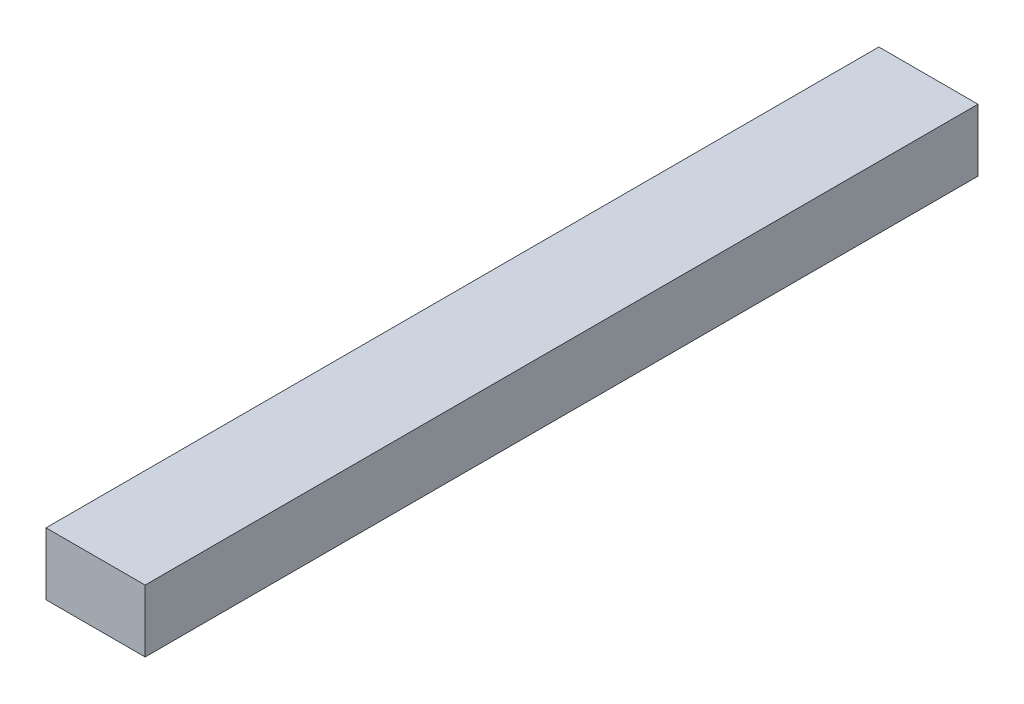
SolidWorks part; units mm, degrees
ref_plane "Front Plane" through (0, 0, 0) normal (0, 0, 1) x (1, 0, 0)
ref_plane "Top Plane" through (0, 0, 0) normal (0, 1, 0) x (1, 0, 0)
ref_plane "Right Plane" through (0, 0, 0) normal (1, 0, 0) x (0, 0, -1)
sketch "Sketch1" plane through (0, 0, 0) normal (0, 0, 1) x (1, 0, 0)
  line L7 (-35, -22) -> (35, -22)
  line L8 (-35, -22) -> (-35, 22)
  line L9 (-35, 22) -> (35, 22)
  line L10 (35, -22) -> (35, 22)
  line L11 (-35, -22) -> (35, 22) construction
  line L12 (-35, 22) -> (35, -22) construction
  point P10 (0, 0)
  dimension "D1" = 70
  dimension "D2" = 44
extrude "Boss-Extrude1" add sketch "Sketch1" along normal up to surface (294 mm away) and the other way up to surface (294 mm away)
